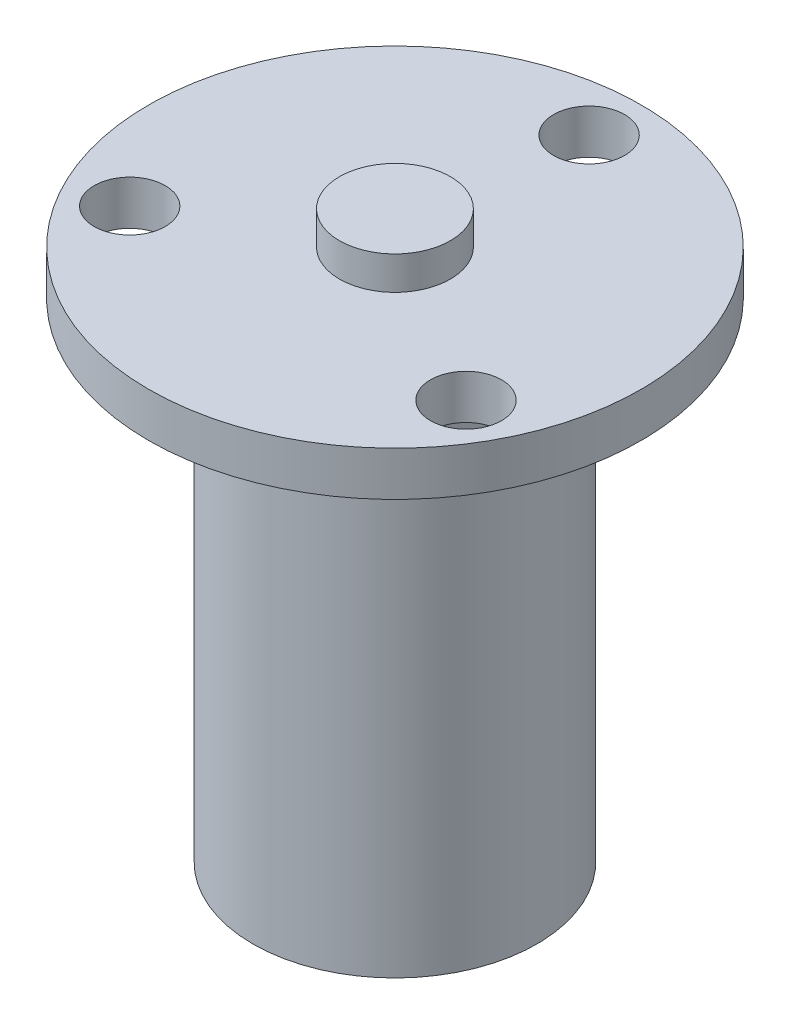
SolidWorks part; units mm, degrees
ref_plane "前视基准面" through (0, 0, 0) normal (0, 0, 1) x (1, 0, 0)
ref_plane "上视基准面" through (0, 0, 0) normal (0, 1, 0) x (1, 0, 0)
ref_plane "右视基准面" through (0, 0, 0) normal (1, 0, 0) x (0, 0, -1)
sketch "草图1" plane through (0, 0, 0) normal (0, 1, 0) x (1, 0, 0)
  circle A0 centre (0, 0) radius 6.4
extrude "凸台-拉伸1" add sketch "草图1" along normal blind 22
sketch "草图2" plane through (0, 22, 0) normal (0, 1, 0) x (1, 0, 0)
  circle A0 centre (0, 0) radius 11.1
  circle A2 centre (0, 8.75) radius 1.6
  circle A3 centre (7.5777, -4.375) radius 1.6
  circle A4 centre (-7.5777, -4.375) radius 1.6
  point P12 (0, 0)
  dimension "D1" = 3
extrude "凸台-拉伸3" add sketch "草图2" along normal blind 2
sketch "草图3" plane through (0, 24, 0) normal (0, 1, 0) x (1, 0, 0)
  circle A0 centre (0, 0) radius 2.5
extrude "凸台-拉伸4" add sketch "草图3" along normal blind 1.5
